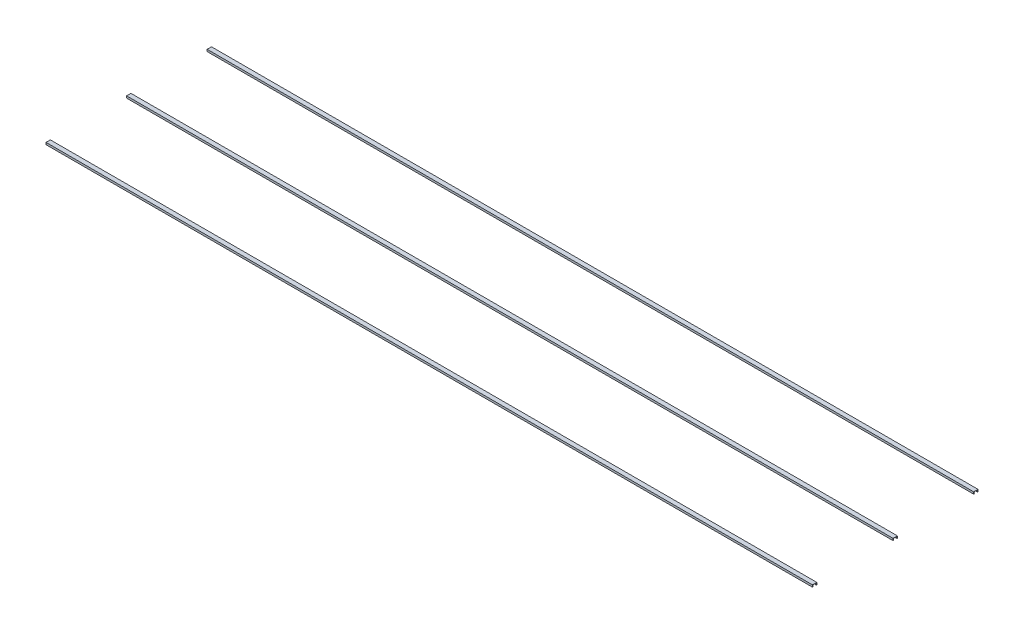
SolidWorks part; units mm, degrees
material "ABS"
ref_plane "Front" through (0, 0, 0) normal (0, 0, 1) x (1, 0, 0)
ref_plane "Top" through (0, 0, 0) normal (0, 1, 0) x (1, 0, 0)
ref_plane "Right" through (0, 0, 0) normal (1, 0, 0) x (0, 0, -1)
sketch "Sketch1" plane through (0, 0, 0) normal (1, 0, 0) x (0, 0, -1)
  line L0 (0, 0) -> (-266, 0)
  line L5 (-5.15, -3.35) -> (-5.15, -2.0232)
  line L6 (-7.15, 3.35) -> (7.15, 3.35)
  line L7 (0, 0) -> (266, 0)
  line L8 (-7.15, 3.35) -> (-7.15, -3.35)
  line L9 (-7.15, -3.35) -> (-5.15, -3.35)
  line L10 (7.15, 3.35) -> (7.15, -3.35)
  line L11 (271.95, -0.7815) -> (271.95, -2.0232)
  line L12 (271.95, -2.0232) -> (271.15, -2.0232)
  line L13 (-5.15, -2.0232) -> (-5.95, -2.0232)
  line L14 (-5.95, -2.0232) -> (-5.95, -0.7815)
  line L15 (-5.95, -0.7815) -> (-5.15, -0.7815)
  line L16 (-5.15, -0.7815) -> (-5.15, 0.2763)
  line L17 (-5.15, 0.2763) -> (-5.95, 0.2763)
  line L18 (-5.95, 0.2763) -> (-5.95, 2.3918)
  line L19 (-5.95, 2.3918) -> (5.95, 2.3918)
  line L20 (5.95, 2.3918) -> (5.95, 0.2763)
  line L21 (5.95, 0.2763) -> (5.15, 0.2763)
  line L22 (5.15, 0.2763) -> (5.15, -0.7815)
  line L23 (5.15, -0.7815) -> (5.95, -0.7815)
  line L24 (5.95, -0.7815) -> (5.95, -2.0232)
  line L26 (5.95, -2.0232) -> (5.15, -2.0232)
  line L27 (5.15, -2.0232) -> (5.15, -3.35)
  line L28 (5.15, -3.35) -> (7.15, -3.35)
  line L29 (271.15, -2.0232) -> (271.15, -3.35)
  line L30 (271.15, -3.35) -> (273.15, -3.35)
  line L31 (273.15, 3.35) -> (273.15, -3.35)
  line L32 (258.85, 3.35) -> (273.15, 3.35)
  line L33 (258.85, 3.35) -> (258.85, -3.35)
  line L34 (258.85, -3.35) -> (260.85, -3.35)
  line L35 (260.85, -3.35) -> (260.85, -2.0232)
  line L36 (260.85, -2.0232) -> (260.05, -2.0232)
  line L37 (260.05, -2.0232) -> (260.05, -0.7815)
  line L38 (260.05, -0.7815) -> (260.85, -0.7815)
  line L39 (260.85, -0.7815) -> (260.85, 0.2763)
  line L40 (260.85, 0.2763) -> (260.05, 0.2763)
  line L41 (260.05, 0.2763) -> (260.05, 2.3918)
  line L42 (260.05, 2.3918) -> (271.95, 2.3918)
  line L43 (271.95, 2.3918) -> (271.95, 0.2763)
  line L44 (271.95, 0.2763) -> (271.15, 0.2763)
  line L45 (271.15, 0.2763) -> (271.15, -0.7815)
  line L46 (271.15, -0.7815) -> (271.95, -0.7815)
  line L47 (5.95, -0.7815) -> (271.95, -0.7815) construction
  line L48 (-260.05, -0.7815) -> (-260.05, -2.0232)
  line L49 (-260.05, -2.0232) -> (-260.85, -2.0232)
  line L50 (-260.85, -2.0232) -> (-260.85, -3.35)
  line L51 (-260.85, -3.35) -> (-258.85, -3.35)
  line L52 (-258.85, 3.35) -> (-258.85, -3.35)
  line L53 (-273.15, 3.35) -> (-258.85, 3.35)
  line L54 (-273.15, 3.35) -> (-273.15, -3.35)
  line L55 (-273.15, -3.35) -> (-271.15, -3.35)
  line L56 (-271.15, -3.35) -> (-271.15, -2.0232)
  line L57 (-271.15, -2.0232) -> (-271.95, -2.0232)
  line L58 (-271.95, -2.0232) -> (-271.95, -0.7815)
  line L59 (-271.95, -0.7815) -> (-271.15, -0.7815)
  line L60 (-271.15, -0.7815) -> (-271.15, 0.2763)
  line L61 (-271.15, 0.2763) -> (-271.95, 0.2763)
  line L62 (-271.95, 0.2763) -> (-271.95, 2.3918)
  line L63 (-271.95, 2.3918) -> (-260.05, 2.3918)
  line L64 (-260.05, 2.3918) -> (-260.05, 0.2763)
  line L65 (-260.05, 0.2763) -> (-260.85, 0.2763)
  line L66 (-260.85, 0.2763) -> (-260.85, -0.7815)
  line L67 (-260.85, -0.7815) -> (-260.05, -0.7815)
  line L68 (271.95, -0.7815) -> (-260.05, -0.7815) construction
  point P0 (0, 0)
  point P13 (5.15, -0.2526)
  dimension "D1" = 266
  dimension "D2" = 266
  dimension "D3" = 14.3
  dimension "D4" = 6.7
  dimension "D5" = 1.2
  dimension "D6" = 2
  dimension "D7" = 1.2
  dimension "D8" = 2
  dimension "D9" = 266
  dimension "D11" = 532
  dimension "D10" = 2
extrude "Boss-Extrude1" add sketch "Sketch1" along normal blind 2530 contours L65 L66 L0 L52 L53 L54 L55 L56 L57 L58 L59 L60 L61 L62 L63 L64 | L21 L22 L7 L10 L6 L8 L0 L16 L17 L18 L19 L20 | L27 L28 L10 L7 L22 L23 L24 L26 | L15 L16 L0 L8 L9 L5 L13 L14 | L45 L46 L11 L12 L29 L30 L31 L32 L33 L7 L39 L40 L41 L42 L43 L44 | L38 L39 L7 L33 L34 L35 L36 L37 | L66 L67 L48 L49 L50 L51 L52 L0
ref_plane "Plane1" through (0, 0, 0) normal (0, 0, -1) x (-1, 0, 0)
